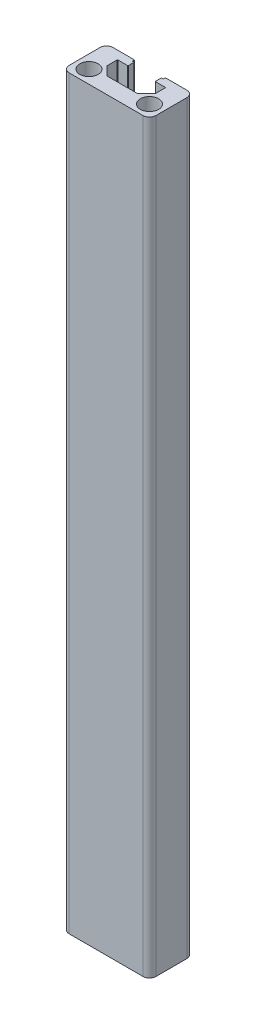
SolidWorks part; units mm, degrees
material "氧化铝"
ref_plane "前视基准面" through (0, 0, 0) normal (0, 0, 1) x (1, 0, 0)
ref_plane "上视基准面" through (0, 0, 0) normal (0, 1, 0) x (1, 0, 0)
ref_plane "右视基准面" through (0, 0, 0) normal (1, 0, 0) x (0, 0, -1)
sketch "草图1" plane through (0, 0, 0) normal (0, 1, 0) x (1, 0, 0)
  line L0 (-3.5, 10) -> (-3.5, 9.5)
  line L1 (-8.4, 10) -> (-3.5, 10)
  line L2 (-9.9, 8.5) -> (-9.9, 1.5)
  line L3 (-8.4, 0) -> (8.4, 0)
  line L4 (9.9, 8.5) -> (9.9, 1.5)
  line L5 (-3.5, 9.5) -> (-3.1, 9.5)
  line L6 (-3.1, 9.5) -> (-3.1, 8.1)
  line L7 (-3.1, 8.1) -> (-5.5, 8.1)
  line L8 (-5.5, 8.1) -> (-5.5, 5.7012)
  line L9 (-5.5, 5.7012) -> (-3.4988, 3.7)
  line L10 (-3.4988, 3.7) -> (3.4988, 3.7)
  line L11 (3.4988, 3.7) -> (5.5, 5.7012)
  line L12 (5.5, 5.7012) -> (5.5, 8.1)
  line L13 (5.5, 8.1) -> (3.1, 8.1)
  line L14 (3.1, 8.1) -> (3.1, 9.5)
  line L15 (3.1, 9.5) -> (3.5, 9.5)
  line L16 (3.5, 9.5) -> (3.5, 10)
  line L17 (3.5, 10) -> (8.4, 10)
  arc A0 (8.4, 10) -> (9.9, 8.5) centre (8.4, 8.5) cw
  arc A1 (8.4, 0) -> (9.9, 1.5) centre (8.4, 1.5) ccw
  arc A2 (-9.9, 1.5) -> (-8.4, 0) centre (-8.4, 1.5) ccw
  arc A3 (-8.4, 10) -> (-9.9, 8.5) centre (-8.4, 8.5) ccw
  circle A4 centre (-6.9, 3) radius 2.1
  circle A5 centre (6.9, 3) radius 2.1
  point P0 (0, 0)
  point P8 (9.9, 10)
  point P13 (-9.9, 0)
  point P16 (-9.9, 10)
  dimension "D3" = 1.5
  dimension "D4" = 4.2
  dimension "D15" = 2.9
  dimension "D1" = 19.8
  dimension "D2" = 10
  dimension "D5" = 3
  dimension "D6" = 3
  dimension "D7" = 3
  dimension "D8" = 7
  dimension "D9" = 6.2
  dimension "D10" = 3.5
  dimension "D11" = 0.4
  dimension "D12" = 0.5
  dimension "D13" = 1.4
  dimension "D14" = 6.3
  dimension "D16" = 2.9
  dimension "D17" = 5.5
  dimension "D18" = 11
  dimension "D19" = 135
extrude "凸台-拉伸1" add sketch "草图1" along normal mid plane 170
fillet "圆角1" radius 0.1 14 edges at (5.5, 0, -8.1) (5.5, 0, -5.7012) (3.4988, 0, -3.7) (-3.4988, 0, -3.7) (-5.5, 0, -5.7012) (-5.5, 0, -8.1) (-3.1, 0, -8.1) (3.1, 0, -8.1) (3.1, 0, -9.5) (3.5, 0, -9.5) (3.5, 0, -10) (-3.5, 0, -9.5) (-3.1, 0, -9.5) (-3.5, 0, -10)
